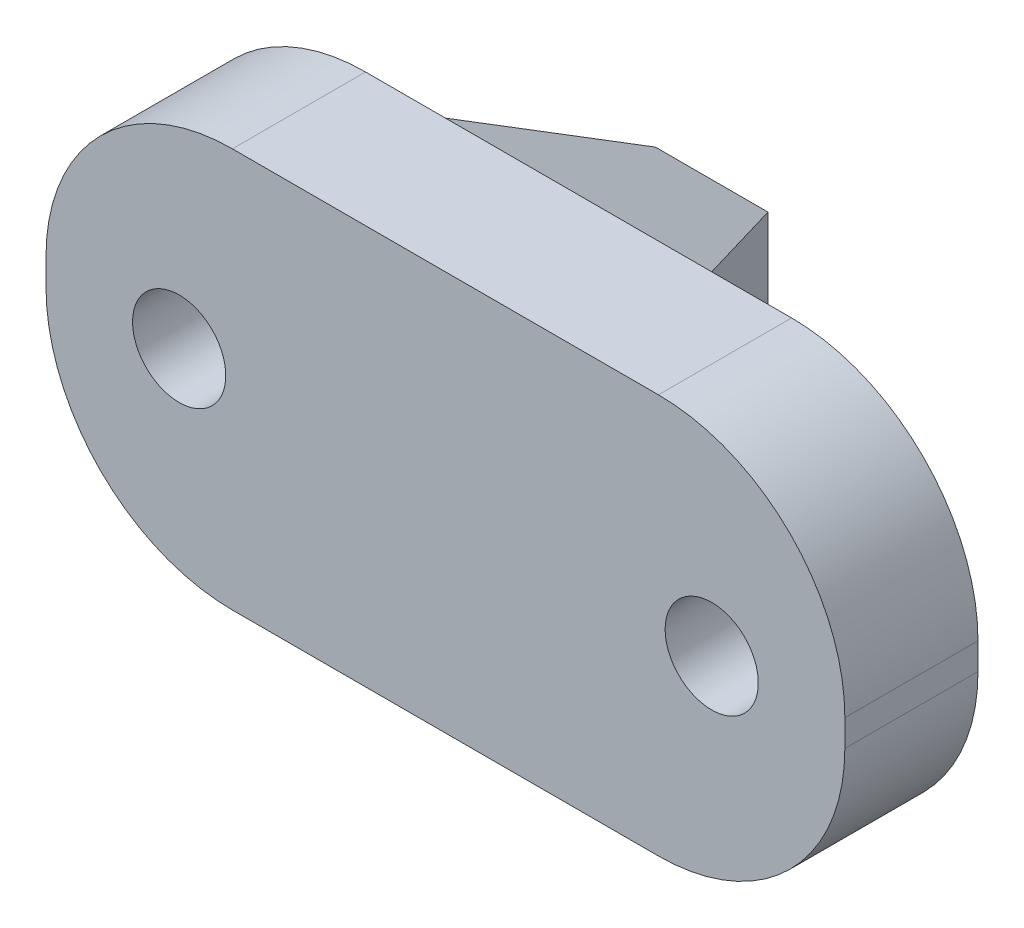
SolidWorks part; units mm, degrees
ref_plane "Front Plane" through (0, 0, 0) normal (0, 0, 1) x (1, 0, 0)
ref_plane "Top Plane" through (0, 0, 0) normal (0, 1, 0) x (1, 0, 0)
ref_plane "Right Plane" through (0, 0, 0) normal (1, 0, 0) x (0, 0, -1)
sketch "Sketch1" plane through (0, 0, 0) normal (0, 1, 0) x (1, 0, 0)
  line L0 (-15, 0) -> (15, 0)
  line L1 (15, 0) -> (15, 5)
  line L2 (15, 5) -> (5, 5)
  line L3 (5, 5) -> (2.1132, 10)
  line L4 (2.1132, 10) -> (-2.1132, 10)
  line L5 (-2.1132, 10) -> (-5, 5)
  line L6 (-5, 5) -> (-15, 5)
  line L7 (-15, 5) -> (-15, 0)
  point P3 (0, 10)
  dimension "D1" = 120
  dimension "D2" = 5
  dimension "D3" = 30
  dimension "D4" = 5
  dimension "D5" = 10
extrude "Boss-Extrude1" add sketch "Sketch1" along normal blind 15
sketch "Sketch11" plane through (0, 0, -5) normal (0, 0, -1) x (-1, 0, 0)
  line L0 (-15, 0) -> (-5, 0) construction
  line L1 (-15, 15) -> (-15, 0) construction
  line L2 (15, 15) -> (15, 0) construction
  circle A0 centre (-10, 7.5) radius 1.75
  circle A1 centre (10, 7.5) radius 1.75
  point P10 (0, 0)
  dimension "D4" = 3.5
  dimension "D1" = 7.5
  dimension "D2" = 5
  dimension "D3" = 5
extrude "Cut-Extrude1" cut sketch "Sketch11" against normal blind 15
sketch "Sketch12" plane through (0, 0, -5) normal (0, 0, -1) x (-1, 0, 0)
  circle A0 centre (-10, 7.5) radius 3
  circle A1 centre (10, 7.5) radius 3
  dimension "D1" = 6
extrude "Cut-Extrude2" cut sketch "Sketch12" against normal blind 2
chamfer "Chamfer1" distance 2 distance2 5 1 edges at (0, 15, -10)
chamfer "Chamfer2" distance 5 distance2 2 1 edges at (0, 0, -10)
sketch "Sketch13" plane through (15, 0, 0) normal (1, 0, 0) x (0, 0, -1)
  line L0 (5, 15) -> (5, 0) construction
  line L1 (5, 10) -> (8, 10)
  line L2 (5, 10) -> (5, 5)
  line L3 (5, 5) -> (8, 5)
  line L4 (8, 10) -> (8, 5)
  line L5 (10, 13) -> (10, 2) construction
  point P6 (8, 7.5)
  point P9 (10, 7.5)
  dimension "D1" = 5
  dimension "D2" = 3
extrude "Cut-Extrude3" cut sketch "Sketch13" against normal through all
fillet "Fillet1" radius 7 4 edges at (-15, 0, -2.5) (-15, 15, -2.5) (15, 0, -2.5) (15, 15, -2.5)
